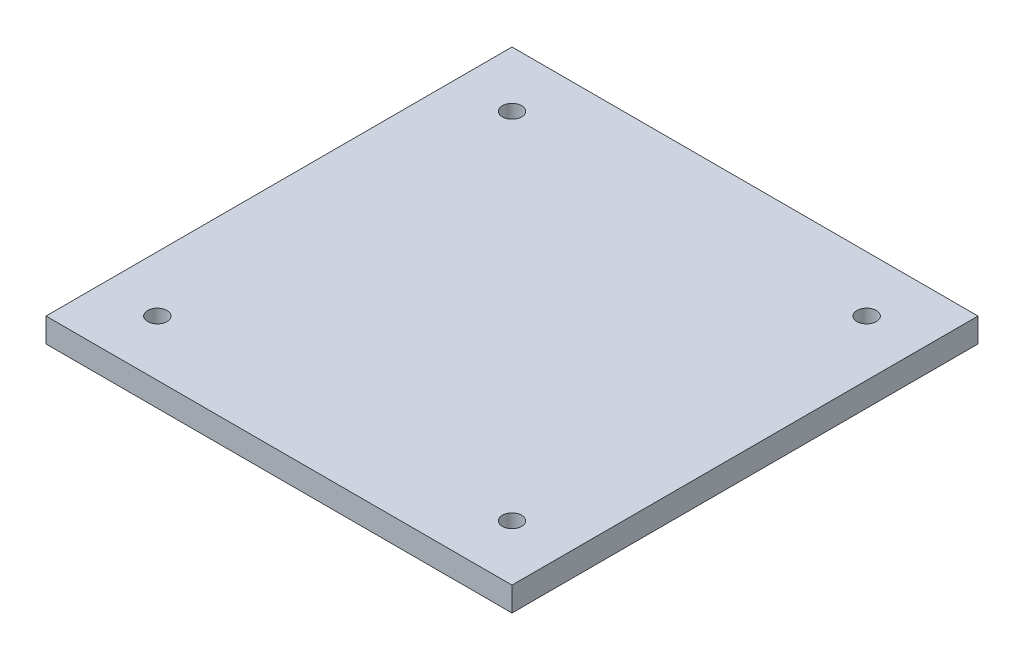
SolidWorks part; units mm, degrees
ref_plane "Front Plane" through (0, 0, 0) normal (0, 0, 1) x (1, 0, 0)
ref_plane "Top Plane" through (0, 0, 0) normal (0, 1, 0) x (1, 0, 0)
ref_plane "Right Plane" through (0, 0, 0) normal (1, 0, 0) x (0, 0, -1)
sketch "Sketch1" plane through (0, 0, 0) normal (0, 1, 0) x (1, 0, 0)
  line L1 (-19.5845, 13.0472) -> (18.9155, 13.0472)
  line L2 (-19.5845, 13.0472) -> (-19.5845, -25.4528)
  line L3 (-19.5845, -25.4528) -> (18.9155, -25.4528)
  line L4 (18.9155, 13.0472) -> (18.9155, -25.4528)
  dimension "D1" = 38.5
  dimension "D2" = 38.5
extrude "Boss-Extrude1" add sketch "Sketch1" along normal blind 2
hole_wizard "M2x0.4 Tapped Hole1" positions "3DSketch2" profile "Sketch3" tap size "M2x0.4" standard "ANSI Metric" end condition up to next
sketch3d "3DSketch2"
  line L0 (18.9155, 2, -13.0472) -> (-19.5845, 2, -13.0472) construction
  line L1 (-19.5845, 2, -13.0472) -> (-19.5845, 2, 25.4528) construction
  line L2 (-19.5845, 2, 25.4528) -> (18.9155, 2, 25.4528) construction
  line L3 (18.9155, 2, 25.4528) -> (18.9155, 2, -13.0472) construction
  point P0 (-14.9845, 2, -8.4472)
  point P2 (14.3155, 2, 20.8528)
  point P4 (14.3155, 2, -8.4472)
  point P6 (-14.9845, 2, 20.8528)
  dimension "D1" = 4.6
  dimension "D2" = 4.6
  dimension "D3" = 4.6
  dimension "D4" = 4.6
  dimension "D5" = 4.6
  dimension "D6" = 4.6
  dimension "D7" = 4.6
  dimension "D8" = 4.6
sketch "Sketch3" plane through (-14.9845, 2, -8.4472) normal (1, 0, 0) x (0, 0, 1)
  line L0 (0, 0) -> (0, 2)
  line L1 (0, 2) -> (0.8, 2)
  line L2 (0.8, 2) -> (0.8, 0)
  line L5 (0.8, 0) -> (0, 0)
  line L11 (0, -6.35) -> (0, 107.95) construction
  dimension "Thread Major Dia." = 1.6
  dimension "Thru Tap Drill Depth" = 2
equation "\"side length\" = 38.5"
equation "\"hole offset\"= 4.6"
equation "\"D1@Sketch1\"=\"side length\""
equation "\"D2@Sketch1\"=\"side length\""
equation "\"D1@3DSketch2\"=\"hole offset\""
equation "\"D2@3DSketch2\"=\"hole offset\""
equation "\"D3@3DSketch2\"=\"hole offset\""
equation "\"D4@3DSketch2\"=\"hole offset\""
equation "\"D5@3DSketch2\"=\"hole offset\""
equation "\"D6@3DSketch2\"=\"hole offset\""
equation "\"D7@3DSketch2\"=\"hole offset\""
equation "\"D8@3DSketch2\"=\"hole offset\""
